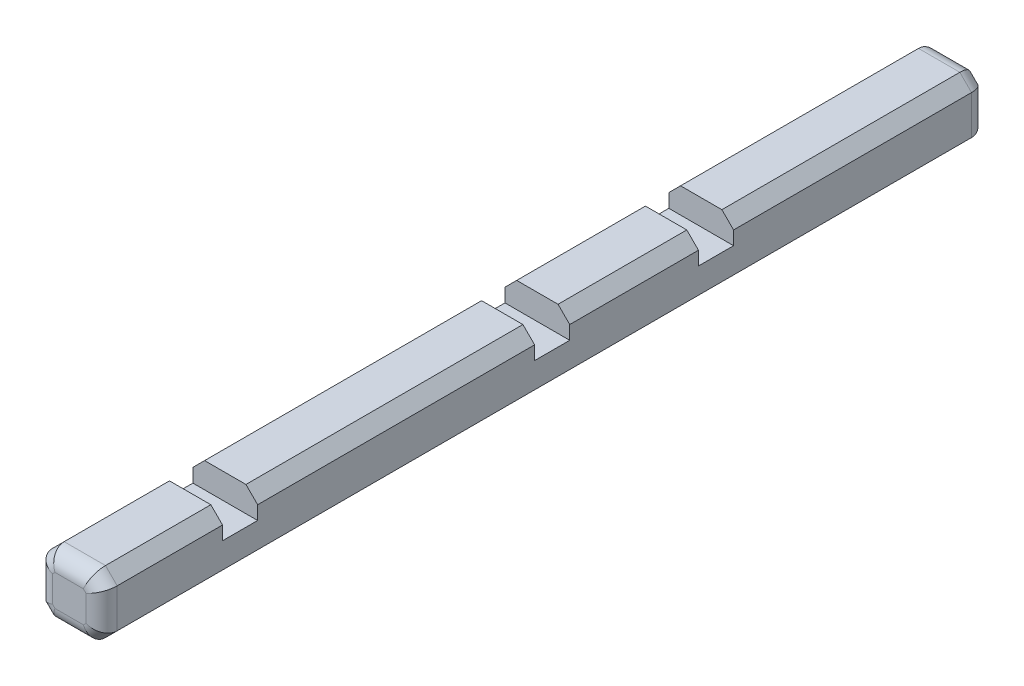
SolidWorks part; units mm, degrees
ref_plane "Front Plane" through (0, 0, 0) normal (0, 0, 1) x (1, 0, 0)
ref_plane "Top Plane" through (0, 0, 0) normal (0, 1, 0) x (1, 0, 0)
ref_plane "Right Plane" through (0, 0, 0) normal (1, 0, 0) x (0, 0, -1)
sketch "Sketch1" plane through (0, 0, 0) normal (0, 0, 1) x (1, 0, 0)
  line L1 (4.15, -4) -> (-4.15, -4)
  line L2 (4.15, -4) -> (4.15, 4)
  line L3 (4.15, 4) -> (-4.15, 4)
  line L4 (-4.15, -4) -> (-4.15, 4)
  point P0 (0, 4)
  point P1 (-4.15, 0)
  dimension "D1" = 8.3
  dimension "D2" = 8
extrude "Boss-Extrude1" add sketch "Sketch1" along normal blind 113.5
chamfer "Chamfer2" distance 1.5 angle 45 4 edges at (4.15, -4, 56.75) (-4.15, -4, 56.75) (4.15, 4, 56.75) (-4.15, 4, 56.75)
sketch "Sketch2" plane through (0, 0, 0) normal (0, 1, 0) x (1, 0, 0)
  line L0 (2.65, -113.5) -> (-2.65, -113.5) construction
  point P0 (0, -58)
  point P3 (0, -113.5)
  point P4 (0, -37)
  point P5 (0, -98)
  dimension "D1" = 55.5
  dimension "D2" = 15.5
  dimension "D3" = 21
ref_plane "Plane1" through (0, 0, 58) normal (0, 0, -1) x (-1, 0, 0)
sketch "Sketch3" plane through (0, 0, 58) normal (0, 0, -1) x (-1, 0, 0)
  line L0 (-4.15, -2.5) -> (-4.15, 2.5) construction
  line L1 (-4.15, 0.75) -> (4.15, 0.75)
  line L2 (-4.15, 0.75) -> (-4.15, 4)
  line L3 (-4.15, 4) -> (4.15, 4)
  line L4 (4.15, 0.75) -> (4.15, 4)
  line L5 (4.15, 2.5) -> (4.15, -2.5) construction
  line L6 (-2.65, 4) -> (2.65, 4) construction
  dimension "D1" = 3.25
extrude "Cut-Extrude1" cut sketch "Sketch3" along normal blind 4.5
ref_plane "Plane2" through (0, 0, 98) normal (0, 0, -1) x (-1, 0, 0)
sketch "Sketch4" plane through (0, 0, 98) normal (0, 0, -1) x (-1, 0, 0)
  line L0 (-4.15, -2.5) -> (-4.15, 2.5) construction
  line L1 (-4.15, 0.75) -> (4.15, 0.75)
  line L2 (-4.15, 0.75) -> (-4.15, 4)
  line L3 (-4.15, 4) -> (4.15, 4)
  line L4 (4.15, 0.75) -> (4.15, 4)
  line L5 (4.15, 2.5) -> (4.15, -2.5) construction
  line L6 (-2.65, 4) -> (2.65, 4) construction
  dimension "D1" = 3.25
extrude "Cut-Extrude2" cut sketch "Sketch4" along normal blind 4.5
fillet "Fillet1" radius 2 16 edges at (0, 4, 0) (-4.15, 0, 0) (0, -4, 0) (4.15, 0, 0) (-4.15, 0, 113.5) (0, 4, 113.5) (4.15, 0, 113.5) (0, -4, 113.5) (3.4, 3.25, 0) (-3.4, 3.25, 0) (-3.4, -3.25, 0) (3.4, -3.25, 0) (-3.4, -3.25, 113.5) (-3.4, 3.25, 113.5) (3.4, 3.25, 113.5) (3.4, -3.25, 113.5)
ref_plane "Plane3" through (0, 0, 37) normal (0, 0, -1) x (-1, 0, 0)
sketch "Sketch6" plane through (0, 0, 37) normal (0, 0, -1) x (-1, 0, 0)
  line L1 (-4.15, 4) -> (4.15, 4)
  line L2 (-4.15, 4) -> (-4.15, 0.75)
  line L3 (-4.15, 0.75) -> (4.15, 0.75)
  line L4 (4.15, 4) -> (4.15, 0.75)
extrude "Cut-Extrude3" cut sketch "Sketch6" along normal blind 4.5
equation "\"thiccness\"=4.5"
equation "\"D1@Cut-Extrude1\"=\"thiccness\""
equation "\"cut\"=3.25"
equation "\"D1@Sketch4\"=\"cut\""
equation "\"D1@Cut-Extrude2\"=\"thiccness\""
equation "\"D1@Sketch3\"=\"cut\""
